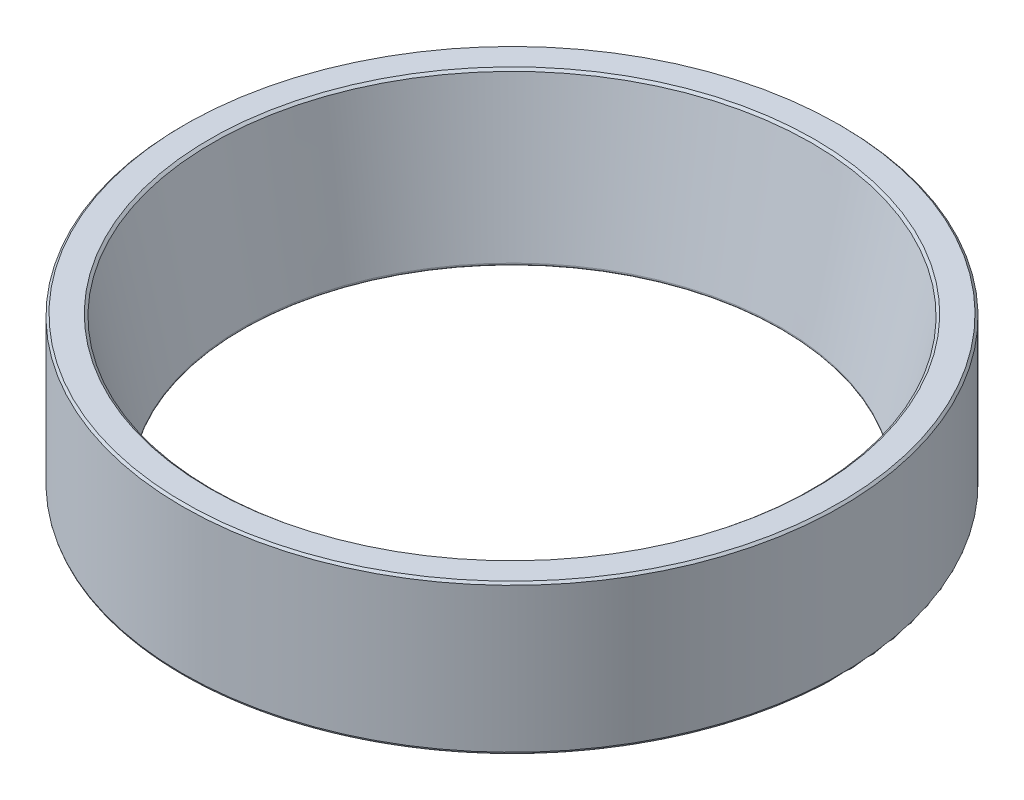
SolidWorks part; units mm, degrees
ref_plane "Ön Düzlem" through (0, 0, 0) normal (0, 0, 1) x (1, 0, 0)
ref_plane "Üst Düzlem" through (0, 0, 0) normal (0, 1, 0) x (1, 0, 0)
ref_plane "Sağ Düzlem" through (0, 0, 0) normal (1, 0, 0) x (0, 0, -1)
sketch "Çizim1" plane through (0, 0, 0) normal (0, 0, 1) x (1, 0, 0)
  line L0 (-25.4974, 0) -> (-30.8, 0)
  line L1 (-31, 0.2) -> (-31, 13.8)
  line L2 (-30.8, 14) -> (-28.45, 14)
  line L3 (-28.2081, 13.8044) -> (-25.3018, 0.2419)
  line L4 (-28.45, 14) -> (-28.2081, 13.8044)
  line L5 (-31, 13.8) -> (-30.8, 14)
  line L6 (0, 0) -> (0, 12.7681) construction
  arc A0 (-30.8, 0) -> (-31, 0.2) centre (-30.8, 0.2) cw
  arc A1 (-25.4974, 0) -> (-25.3018, 0.2419) centre (-25.4974, 0.2) ccw
  point P4 (-31, 14)
  point P5 (-28.25, 14)
  point P11 (-31, 0)
  point P14 (-25.25, 0)
  dimension "D5" = 0.2
  dimension "D1" = 31
  dimension "D2" = 14
  dimension "D3" = 5.75
  dimension "D4" = 2.75
revolve "Döndür1" add sketch "Çizim1" angle 360 about L6
